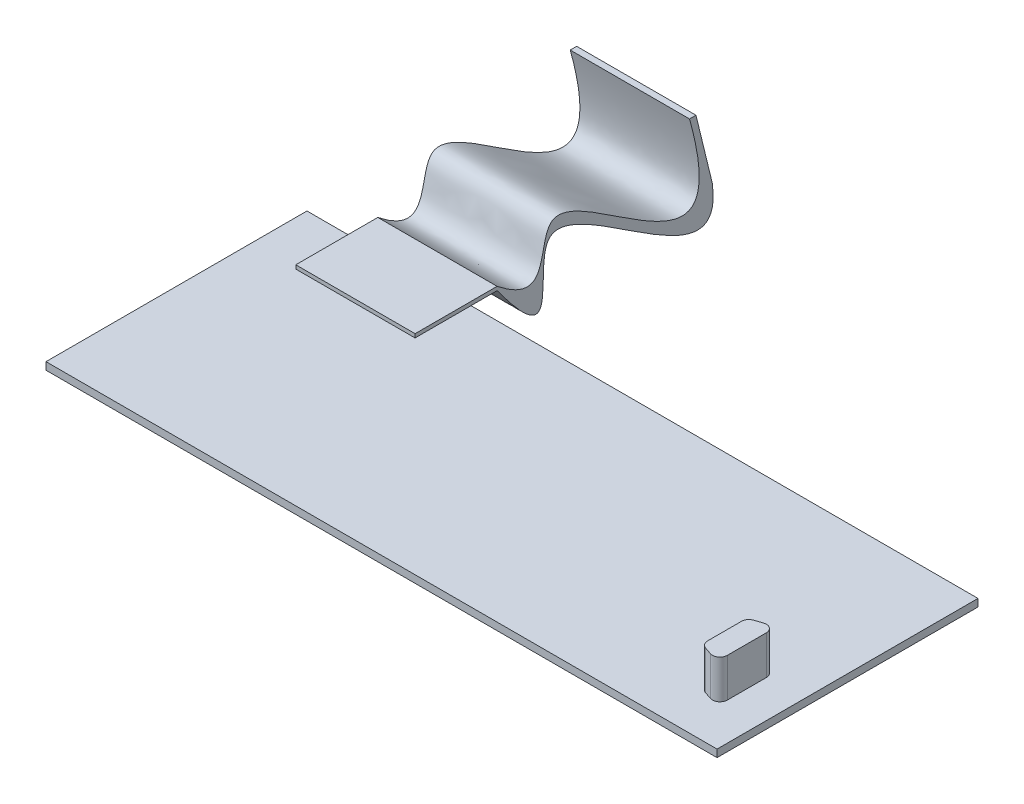
SolidWorks part; units mm, degrees
ref_plane "Front Plane" through (0, 0, 0) normal (0, 0, 1) x (1, 0, 0)
ref_plane "Top Plane" through (0, 0, 0) normal (0, 1, 0) x (1, 0, 0)
ref_plane "Right Plane" through (0, 0, 0) normal (1, 0, 0) x (0, 0, -1)
sketch "Sketch4" plane through (0, 0, 0) normal (0, 1, 0) x (1, 0, 0)
  line L1 (19.05, 107.95) -> (247.65, 107.95)
  line L2 (19.05, 107.95) -> (19.05, 19.05)
  line L3 (19.05, 19.05) -> (247.65, 19.05)
  line L4 (247.65, 107.95) -> (247.65, 19.05)
  dimension "D1" = 19.05
  dimension "D2" = 19.05
  dimension "D3" = 247.65
  dimension "D4" = 107.95
extrude "Boss-Extrude3" add sketch "Sketch4" along normal blind 2.54
sketch "Sketch5" plane through (0, 2.54, 0) normal (0, 1, 0) x (1, 0, 0)
  line L0 (247.65, 107.95) -> (19.05, 107.95) construction
  line L1 (40.64, 97.79) -> (73.66, 97.79)
  line L2 (40.64, 97.79) -> (40.64, 92.71)
  line L3 (40.64, 92.71) -> (73.66, 92.71)
  line L4 (73.66, 97.79) -> (73.66, 92.71)
  line L5 (19.05, 107.95) -> (19.05, 19.05) construction
  dimension "D1" = 33.02
  dimension "D2" = 5.08
  dimension "D3" = 10.16
  dimension "D4" = 21.59
extrude "Boss-Extrude4" add sketch "Sketch5" along normal blind 2.54
sketch "Sketch6" plane through (0, 5.08, 0) normal (0, 1, 0) x (1, 0, 0)
  line L1 (36.83, 114.3) -> (77.47, 114.3)
  line L2 (36.83, 114.3) -> (36.83, 86.36)
  line L3 (36.83, 86.36) -> (77.47, 86.36)
  line L4 (77.47, 114.3) -> (77.47, 86.36)
  line L5 (73.66, 97.79) -> (40.64, 97.79) construction
  line L6 (73.66, 92.71) -> (73.66, 97.79) construction
  dimension "D1" = 27.94
  dimension "D2" = 40.64
  dimension "D3" = 11.43
  dimension "D4" = 3.81
extrude "Boss-Extrude5" add sketch "Sketch6" along normal blind 1.27
sketch "Sketch7" plane through (36.83, 0, 0) normal (-1, 0, 0) x (0, 0, 1)
  line L0 (-187.6452, 0) -> (-182.0556, 22.9559)
  line L1 (-182.0556, 22.9559) -> (-179.8585, 22.9559)
  line L2 (-114.3, 6.35) -> (-114.3, 5.08)
  spline S0 degree 3 poles (-114.3, 6.35) (-133.2981, -8.8191) (-116.5104, 54.6871) (-196.6505, -37.9472) (-179.8585, 22.9559) knots 0 0 0 0 0.345555 1 1 1 1
  spline S1 degree 3 poles (-114.3, 5.08) (-136.9857, -26.135) (-109.5036, 56.2065) (-192.0427, -34.2074) (-187.6452, 0) knots 0 0 0 0 0.382373 1 1 1 1
extrude "Boss-Extrude6" add sketch "Sketch7" against normal blind 40.64
sketch "Sketch8" plane through (0, 2.54, 0) normal (0, 1, 0) x (1, 0, 0)
  line L0 (227.33, 49.53) -> (234.95, 52.07)
  line L1 (234.95, 52.07) -> (234.95, 31.75)
  line L2 (234.95, 31.75) -> (227.33, 34.29)
  line L3 (227.33, 34.29) -> (227.33, 49.53)
  line L4 (247.65, 19.05) -> (247.65, 107.95) construction
  line L5 (19.05, 19.05) -> (247.65, 19.05) construction
  dimension "D1" = 20.32
  dimension "D2" = 15.24
  dimension "D3" = 7.62
  dimension "D4" = 2.54
  dimension "D5" = 12.7
  dimension "D6" = 12.7
extrude "Boss-Extrude7" add sketch "Sketch8" along normal blind 13.208
fillet "Fillet1" radius 2.54 4 edges at (227.33, 9.144, -49.53) (234.95, 9.144, -52.07) (227.33, 9.144, -34.29) (234.95, 9.144, -31.75)
